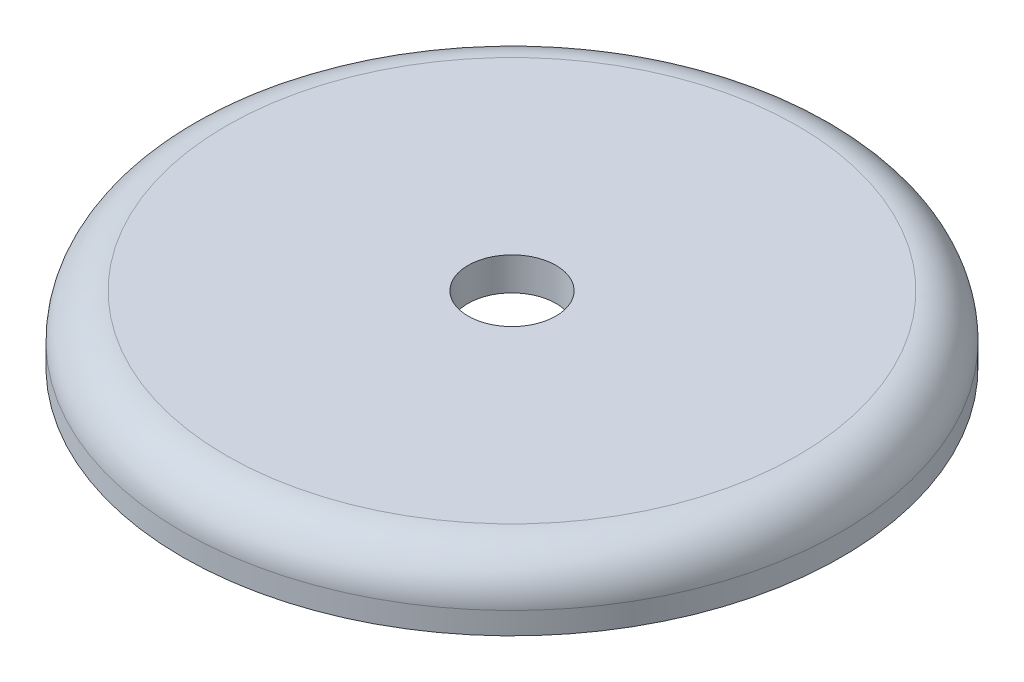
SolidWorks part; units mm, degrees
ref_plane "Front Plane" through (0, 0, 0) normal (0, 0, 1) x (1, 0, 0)
ref_plane "Top Plane" through (0, 0, 0) normal (0, 1, 0) x (1, 0, 0)
ref_plane "Right Plane" through (0, 0, 0) normal (1, 0, 0) x (0, 0, -1)
sketch "Sketch2" plane through (0, 0, 0) normal (0, 0, 1) x (1, 0, 0)
  line L0 (0, 0) -> (15, 0)
  line L1 (0, 0) -> (0, 3)
  line L2 (15, 0) -> (15, 3)
  line L3 (15, 3) -> (0, 3)
  dimension "D1" = 15
  dimension "D2" = 3
  dimension "D3" = 15
revolve "Revolve1" add sketch "Sketch2" angle 360 about L1
sketch "Sketch3" plane through (0, 0, 0) normal (0, -1, 0) x (1, 0, 0)
  circle A0 centre (0, 0) radius 8
  dimension "D1" = 16
extrude "Cut-Extrude1" cut sketch "Sketch3" against normal blind 1.5
sketch "Sketch4" plane through (0, 1.5, 0) normal (0, -1, 0) x (1, 0, 0)
  arc A0 (0, -0.8) -> (0, 0.8) centre (0, 0) ccw construction
  arc A1 (0, 0.8) -> (0, -0.8) centre (0, 0) ccw construction
  arc A2 (0, -0.8) -> (0, 0.8) centre (0, 0) ccw construction
  arc A3 (0, 0.8) -> (0, -0.8) centre (0, 0) ccw construction
  arc A4 (0, -2) -> (0, 2) centre (0, 0) ccw
  arc A5 (0, 2) -> (0, -2) centre (0, 0) ccw
  dimension "D1" = 1.2
extrude "Cut-Extrude2" cut sketch "Sketch4" against normal up to surface (1.5 mm away) up to face at (0, 3, -15)
sketch "Sketch5" plane through (0, 0, 0) normal (0, -1, 0) x (1, 0, 0)
  circle A0 centre (0.41, -10.965) radius 1.6 construction
  circle A1 centre (0.82, 10.965) radius 1.6 construction
  circle A2 centre (0.41, -10.965) radius 1.6 construction
  circle A3 centre (0.82, 10.965) radius 1.6 construction
  circle A4 centre (0.41, -10.965) radius 2.6
  circle A5 centre (0.82, 10.965) radius 2.6
  dimension "D1" = 1
extrude "Cut-Extrude3" cut sketch "Sketch5" against normal blind 1.8
fillet "Fillet1" radius 2 1 edges at (0, 3, -15)
